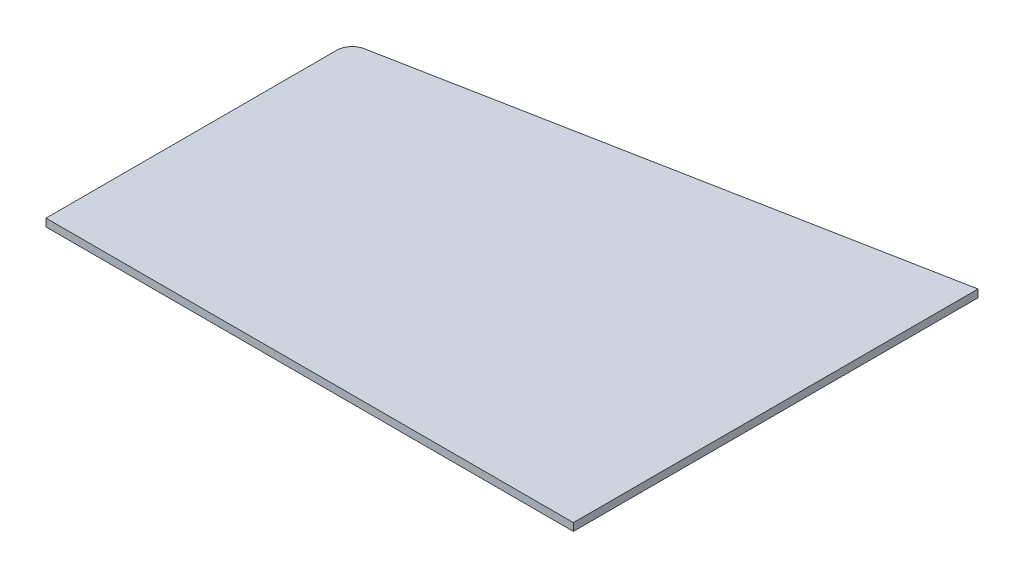
SolidWorks part; units mm, degrees
material "Balsa"
ref_plane "Front Plane" through (0, 0, 0) normal (0, 0, 1) x (1, 0, 0)
ref_plane "Top Plane" through (0, 0, 0) normal (0, 1, 0) x (1, 0, 0)
ref_plane "Right Plane" through (0, 0, 0) normal (1, 0, 0) x (0, 0, -1)
sketch "Sketch1" plane through (0, 0, 0) normal (0, 1, 0) x (1, 0, 0)
  line L0 (0, 0) -> (437.0222, 0)
  line L1 (437.0222, 335.28) -> (10.3078, 253.437)
  line L2 (0, 240.9644) -> (0, 0)
  line L3 (437.0222, 0) -> (437.0222, 335.28)
  arc A0 (10.3078, 253.437) -> (0, 240.9644) centre (12.7, 240.9644) ccw
  point P7 (0, 251.46)
  dimension "D4" = 12.7
  dimension "D1" = 251.46
  dimension "D2" = 437.0222
  dimension "D3" = 335.28
extrude "Boss-Extrude1" add sketch "Sketch1" along normal blind 6.35
